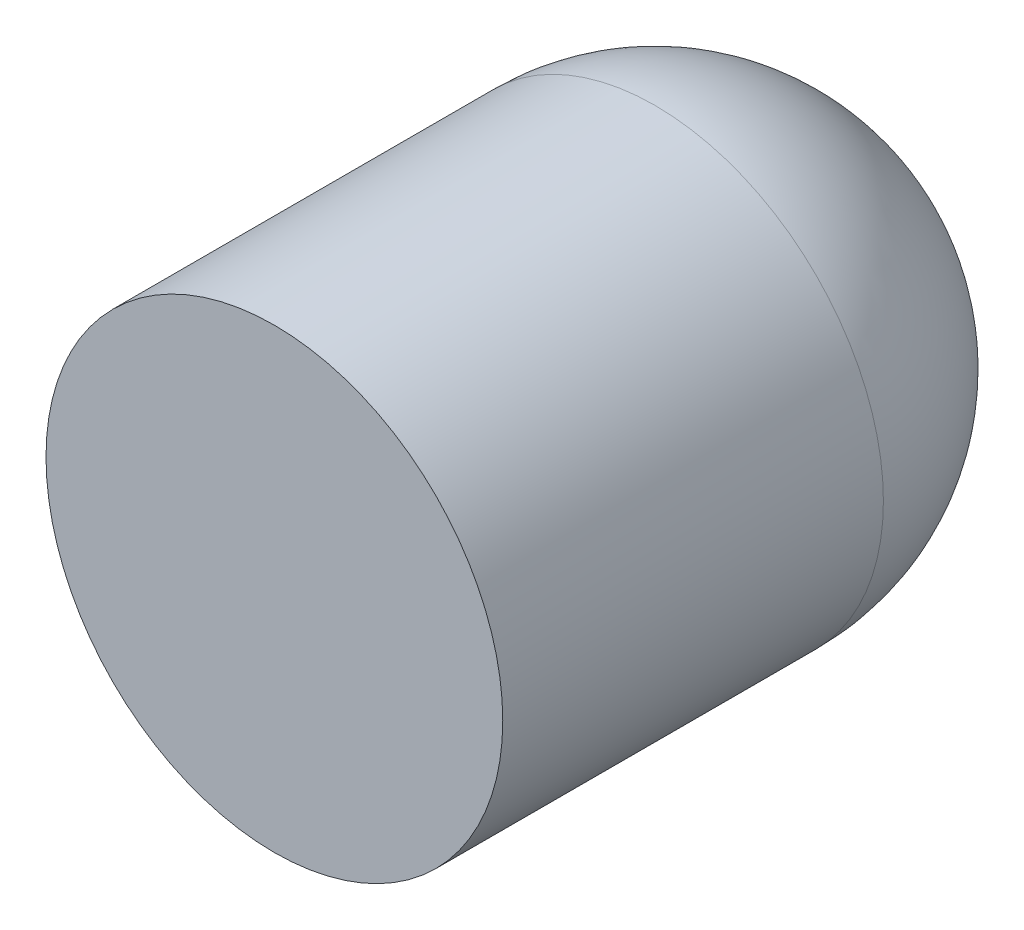
SolidWorks part; units mm, degrees
other "Markup1"
sketch "Sketch3" plane through (-76.2, 76.2, -762) normal (-0.6807, 0.6563, -0.3256) x (-0.115, 0.3432, 0.9322)
ref_plane "Front Plane" through (0, 0, 0) normal (0, 0, 1) x (1, 0, 0)
ref_plane "Top Plane" through (0, 0, 0) normal (0, 1, 0) x (1, 0, 0)
ref_plane "Right Plane"
sketch "Sketch1" plane through (0, 0, 0) normal (1, 0, 0) x (0, 0, -1)
  line L0 (0, 76.2) -> (0, 0)
  line L1 (0, 0) -> (76.2, 0)
  spline S0 degree 4 poles (-7.6202, 75.818) (-7.2589, 75.8543) (-6.5362, 75.9223) (-5.4547, 76.0105) (-3.9985, 76.1005) (-2.6973, 76.1572) (-1.5017, 76.1883) (-0.3268, 76.2018) (0.6113, 76.2004) (1.8643, 76.1819) (3.0567, 76.1425) (4.2871, 76.0835) (5.5089, 76.0047) (6.7304, 75.9063) (7.9499, 75.7883) (9.1675, 75.6507) (10.3826, 75.4935) (12.5044, 75.1843) (16.1238, 74.5374) (21.1925, 73.3194) (27.5957, 71.1862) (33.7637, 68.4462) (39.1345, 65.4854) (43.753, 62.4671) (47.6774, 59.5258) (51.4047, 56.3384) (54.9194, 52.9181) (58.207, 49.2789) (61.2539, 45.4359) (64.0475, 41.405) (66.5762, 37.203) (68.8297, 32.8471) (70.7985, 28.3554) (72.4745, 23.7465) (73.927, 18.779) (75.3485, 12.2827) (76.002, 6.8917) (76.2, 2.6977) (76.2, 0) knots 0 0 0 0 0 0.011395 0.022791 0.034186 0.045582 0.052764 0.059946 0.069569 0.079191 0.088814 0.098436 0.108059 0.117682 0.127304 0.136927 0.14655 0.156172 0.194663 0.252399 0.310135 0.367871 0.406361 0.444852 0.483342 0.521833 0.560323 0.598814 0.637304 0.675795 0.714286 0.752776 0.791266 0.829756 0.868245 0.915252 1 1 1 1 1 construction
  spline S1 degree 4 poles (0, 76.2) (0.2879, 76.2) (0.8609, 76.1967) (1.8643, 76.1819) (3.0567, 76.1425) (4.2871, 76.0835) (5.5089, 76.0047) (6.7304, 75.9063) (7.9499, 75.7883) (9.1675, 75.6507) (10.3826, 75.4935) (12.5044, 75.1843) (16.1238, 74.5374) (21.1925, 73.3194) (27.5957, 71.1862) (33.7637, 68.4462) (39.1345, 65.4854) (43.753, 62.4671) (47.6774, 59.5258) (51.4047, 56.3384) (54.9194, 52.9181) (58.207, 49.2789) (61.2539, 45.4359) (64.0475, 41.405) (66.5762, 37.203) (68.8297, 32.8471) (70.7985, 28.3554) (72.4745, 23.7465) (73.927, 18.779) (75.3485, 12.2827) (76.002, 6.8917) (76.2, 2.6977) (76.2, 0) knots 0.059946 0.059946 0.059946 0.059946 0.059946 0.069569 0.079191 0.088814 0.098436 0.108059 0.117682 0.127304 0.136927 0.14655 0.156172 0.194663 0.252399 0.310135 0.367871 0.406361 0.444852 0.483342 0.521833 0.560323 0.598814 0.637304 0.675795 0.714286 0.752776 0.791266 0.829756 0.868245 0.915252 1 1 1 1 1
ref_axis "Axis1" through (0, 0, -480.06) along (0, 0, 1)
revolve "Revolve1" add sketch "Sketch1" angle 360 about axis through (0, 0, -480.06) along (0, 0, 1)
sketch "Sketch2" plane through (0, 0, 0) normal (0, 0, 1) x (1, 0, 0)
  circle A0 centre (0, 0) radius 76.2
  dimension "D1" = 152.4
extrude "Boss-Extrude1" add sketch "Sketch2" along normal blind 127
equation "\"BodyTubeRadius\"= 3in"
equation "\"ratio\"= 0.5"
equation "\"NoseConeLength\"= \"ratio\" * 2 * \"BodyTubeRadius\""
equation "\"D1@Sketch2\"=2*\"BodyTubeRadius\""
equation "\"BodyTubeLength\"=5"
